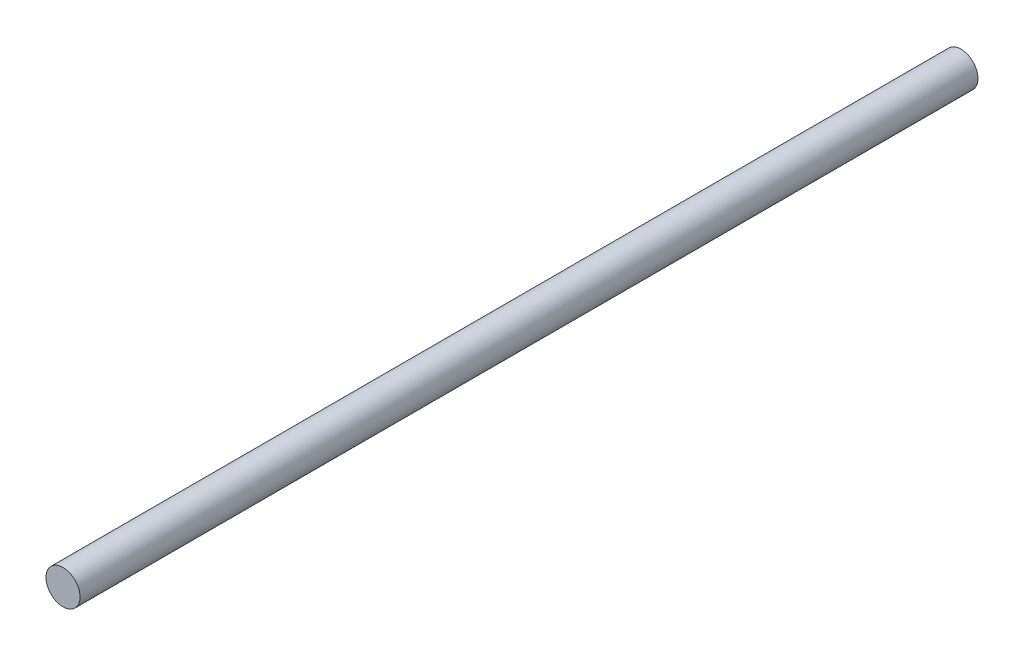
SolidWorks part; units mm, degrees
ref_plane "Ebene vorne" through (0, 0, 0) normal (0, 0, 1) x (1, 0, 0)
ref_plane "Ebene oben" through (0, 0, 0) normal (0, 1, 0) x (1, 0, 0)
ref_plane "Ebene rechts" through (0, 0, 0) normal (1, 0, 0) x (0, 0, -1)
sketch "Skizze1" plane through (0, 0, 0) normal (0, 0, 1) x (1, 0, 0)
  circle A0 centre (0, 0) radius 1.5
  dimension "D1" = 3
extrude "Aufsatz-Linear austragen1" add sketch "Skizze1" along normal blind 30 and the other way blind 49
